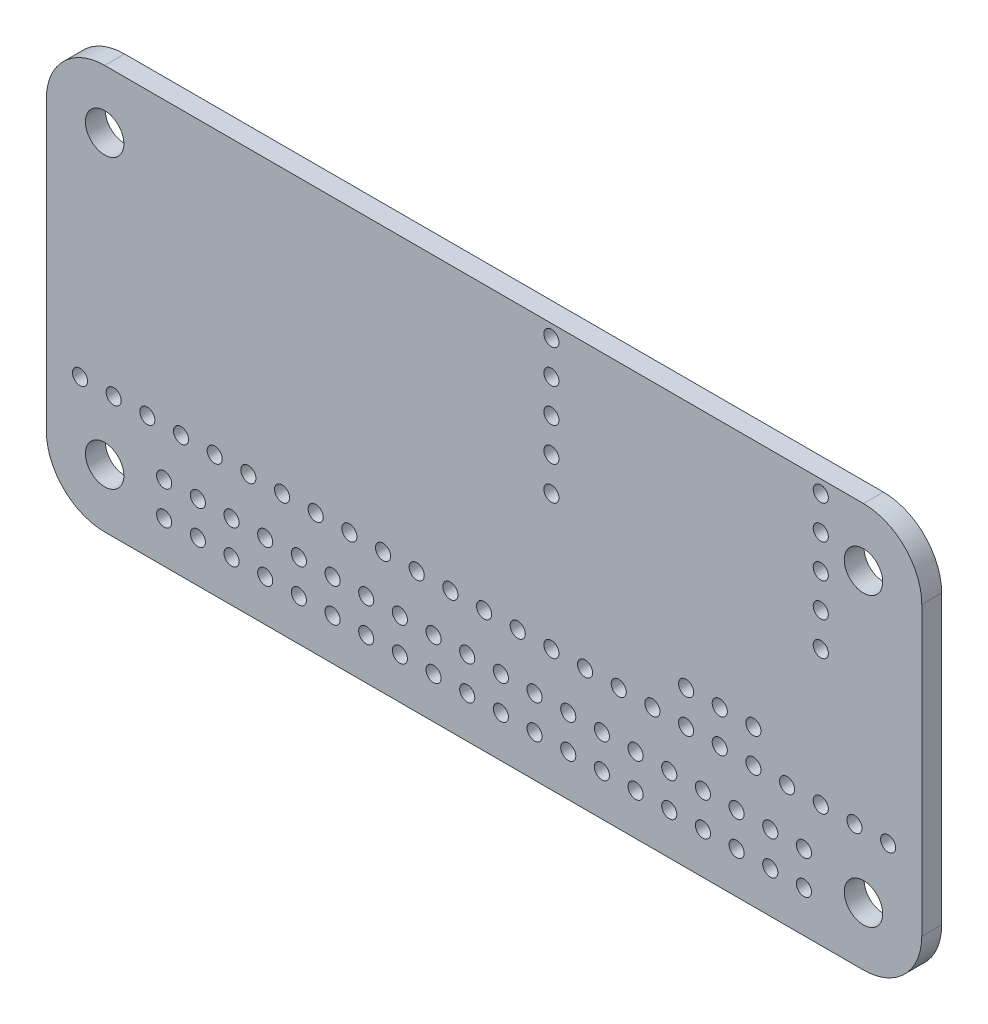
SolidWorks part; units mm, degrees
ref_plane "Alzado" through (0, 0, 0) normal (0, 0, 1) x (1, 0, 0)
ref_plane "Planta" through (0, 0, 0) normal (0, 1, 0) x (1, 0, 0)
ref_plane "Vista lateral" through (0, 0, 0) normal (1, 0, 0) x (0, 0, -1)
sketch "Croquis1" plane through (0, 0, 0) normal (0, 0, 1) x (1, 0, 0)
  line L0 (0, 15.24) -> (0, -15.24) construction
  line L1 (28.62, -15.24) -> (-28.62, -15.24)
  line L2 (33.02, -10.84) -> (33.02, 10.84)
  line L3 (28.62, 15.24) -> (-28.62, 15.24)
  line L4 (-33.02, -10.84) -> (-33.02, 10.84)
  line L5 (33.02, -15.24) -> (-33.02, 15.24) construction
  line L6 (33.02, 15.24) -> (-33.02, -15.24) construction
  line L7 (-33.02, 0) -> (33.02, 0) construction
  line L8 (-28.62, -10.84) -> (28.62, -10.84) construction
  line L9 (-24.13, -12.11) -> (-24.13, -9.57) construction
  line L10 (-24.13, -9.57) -> (-21.59, -9.57) construction
  line L11 (-24.13, -9.57) -> (24.13, -9.57) construction
  arc A0 (33.02, 10.84) -> (28.62, 15.24) centre (28.62, 10.84) ccw
  arc A1 (28.62, -15.24) -> (33.02, -10.84) centre (28.62, -10.84) ccw
  arc A2 (-28.62, -15.24) -> (-33.02, -10.84) centre (-28.62, -10.84) cw
  arc A3 (-28.62, 15.24) -> (-33.02, 10.84) centre (-28.62, 10.84) ccw
  circle A4 centre (-28.62, 10.84) radius 1.45
  circle A5 centre (28.62, 10.84) radius 1.45
  circle A6 centre (28.62, -10.84) radius 1.45
  circle A7 centre (-28.62, -10.84) radius 1.45
  circle A8 centre (-24.13, -9.57) radius 0.57
  circle A9 centre (-24.13, -12.11) radius 0.57
  circle A10 centre (-21.59, -9.57) radius 0.57
  circle A11 centre (-21.59, -12.11) radius 0.57
  circle A12 centre (-19.05, -9.57) radius 0.57
  circle A13 centre (-19.05, -12.11) radius 0.57
  circle A14 centre (-16.51, -9.57) radius 0.57
  circle A15 centre (-16.51, -12.11) radius 0.57
  circle A16 centre (-13.97, -9.57) radius 0.57
  circle A17 centre (-13.97, -12.11) radius 0.57
  circle A18 centre (-11.43, -9.57) radius 0.57
  circle A19 centre (-11.43, -12.11) radius 0.57
  circle A20 centre (-8.89, -9.57) radius 0.57
  circle A21 centre (-8.89, -12.11) radius 0.57
  circle A22 centre (-6.35, -9.57) radius 0.57
  circle A23 centre (-6.35, -12.11) radius 0.57
  circle A24 centre (-3.81, -9.57) radius 0.57
  circle A25 centre (-3.81, -12.11) radius 0.57
  circle A26 centre (-1.27, -9.57) radius 0.57
  circle A27 centre (-1.27, -12.11) radius 0.57
  circle A28 centre (1.27, -9.57) radius 0.57
  circle A29 centre (1.27, -12.11) radius 0.57
  circle A30 centre (3.81, -9.57) radius 0.57
  circle A31 centre (3.81, -12.11) radius 0.57
  circle A32 centre (6.35, -9.57) radius 0.57
  circle A33 centre (6.35, -12.11) radius 0.57
  circle A34 centre (8.89, -9.57) radius 0.57
  circle A35 centre (8.89, -12.11) radius 0.57
  circle A36 centre (11.43, -9.57) radius 0.57
  circle A37 centre (11.43, -12.11) radius 0.57
  circle A38 centre (13.97, -9.57) radius 0.57
  circle A39 centre (13.97, -12.11) radius 0.57
  circle A40 centre (16.51, -9.57) radius 0.57
  circle A41 centre (16.51, -12.11) radius 0.57
  circle A42 centre (19.05, -9.57) radius 0.57
  circle A43 centre (19.05, -12.11) radius 0.57
  circle A44 centre (21.59, -9.57) radius 0.57
  circle A45 centre (21.59, -12.11) radius 0.57
  circle A46 centre (24.13, -9.57) radius 0.57
  circle A47 centre (24.13, -12.11) radius 0.57
  point P0 (0, 0)
  point P29 (-24.13, -10.84)
  point P31 (0, -9.57)
  dimension "D3" = 4.4
  dimension "D4" = 2.9
  dimension "D6" = 1.14
  dimension "D1" = 66.04
  dimension "D2" = 30.48
  dimension "D5" = 2.54
  dimension "D8" = 2.54
  dimension "D7" = 20
extrude "Saliente-Extruir1" add sketch "Croquis1" along normal blind 1.5
sketch "Croquis2" plane through (0, 0, 0) normal (0, 0, -1) x (-1, 0, 0)
  line L0 (0, 15.24) -> (0, -15.24) construction
  line L1 (-28.62, 15.24) -> (28.62, 15.24) construction
  line L2 (28.62, -15.24) -> (-28.62, -15.24) construction
  line L3 (20.32, -6.04) -> (20.32, -3.5) construction
  circle A0 centre (-30.48, -6.04) radius 0.57
  circle A1 centre (-27.94, -6.04) radius 0.57
  circle A2 centre (-25.4, -6.04) radius 0.57
  circle A3 centre (-22.86, -6.04) radius 0.57
  circle A4 centre (-20.32, -6.04) radius 0.57
  circle A5 centre (-17.78, -6.04) radius 0.57
  circle A6 centre (-15.24, -6.04) radius 0.57
  circle A7 centre (-12.7, -6.04) radius 0.57
  circle A8 centre (-10.16, -6.04) radius 0.57
  circle A9 centre (-7.62, -6.04) radius 0.57
  circle A10 centre (-5.08, -6.04) radius 0.57
  circle A11 centre (-2.54, -6.04) radius 0.57
  circle A12 centre (0, -6.04) radius 0.57
  circle A13 centre (2.54, -6.04) radius 0.57
  circle A14 centre (5.08, -6.04) radius 0.57
  circle A15 centre (7.62, -6.04) radius 0.57
  circle A16 centre (10.16, -6.04) radius 0.57
  circle A17 centre (12.7, -6.04) radius 0.57
  circle A18 centre (15.24, -6.04) radius 0.57
  circle A19 centre (17.78, -6.04) radius 0.57
  circle A20 centre (20.32, -6.04) radius 0.57
  circle A21 centre (22.86, -6.04) radius 0.57
  circle A22 centre (25.4, -6.04) radius 0.57
  circle A23 centre (27.94, -6.04) radius 0.57
  circle A24 centre (30.48, -6.04) radius 0.57
  circle A58 centre (-5.08, 14.28) radius 0.57
  circle A59 centre (-25.4, 14.28) radius 0.57
  circle A60 centre (-5.08, 11.74) radius 0.57
  circle A61 centre (-25.4, 11.74) radius 0.57
  circle A62 centre (-5.08, 9.2) radius 0.57
  circle A63 centre (-25.4, 9.2) radius 0.57
  circle A64 centre (-5.08, 6.66) radius 0.57
  circle A65 centre (-25.4, 6.66) radius 0.57
  circle A66 centre (-5.08, 4.12) radius 0.57
  circle A67 centre (-25.4, 4.12) radius 0.57
  circle A68 centre (-15.24, -3.5) radius 0.57
  circle A69 centre (-17.78, -3.5) radius 0.57
  circle A70 centre (-20.32, -3.5) radius 0.57
  dimension "D1" = 1.14
  dimension "D3" = 9.2
  dimension "D4" = 2.54
  dimension "D6" = 2.54
  dimension "D2" = 25
extrude "Cortar-Extruir1" cut sketch "Croquis2" against normal blind 10
